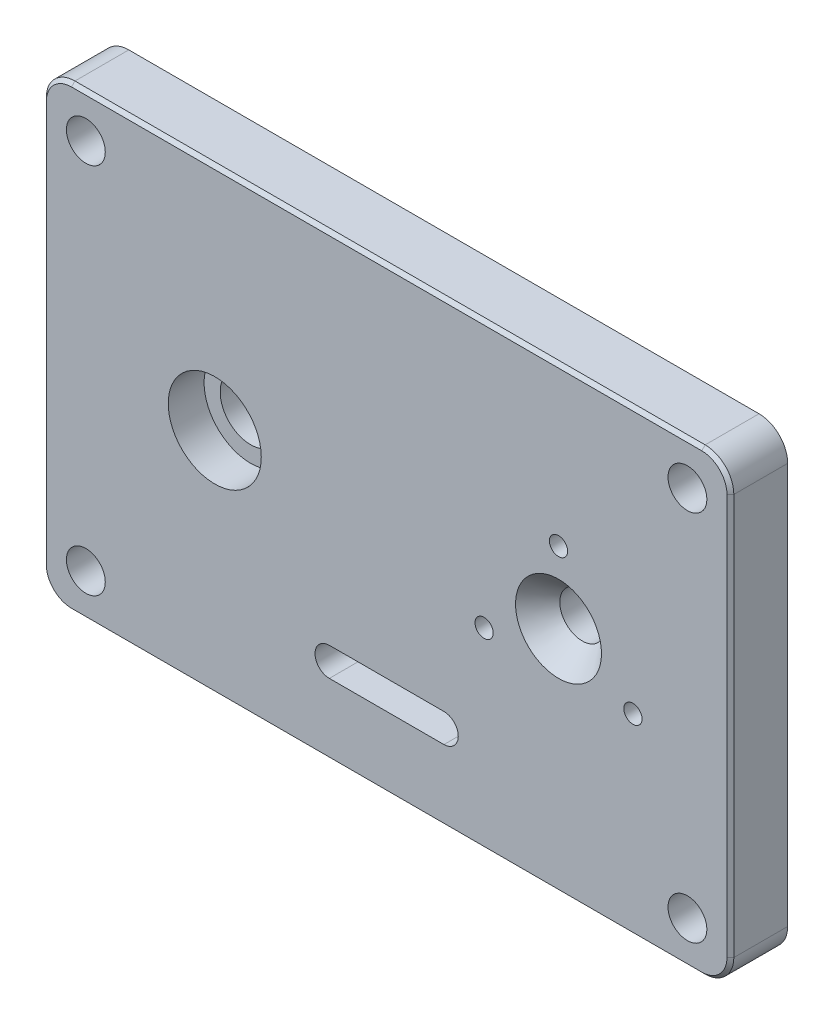
SolidWorks part; units mm, degrees
ref_plane "前视基准面" through (0, 0, 0) normal (0, 0, 1) x (1, 0, 0)
ref_plane "上视基准面" through (0, 0, 0) normal (0, 1, 0) x (1, 0, 0)
ref_plane "右视基准面" through (0, 0, 0) normal (1, 0, 0) x (0, 0, -1)
sketch "草图1" plane through (0, 0, 0) normal (0, 0, 1) x (1, 0, 0)
  line L0 (6.35, 0) -> (146.05, 0)
  line L1 (152.4, 6.35) -> (152.4, 95.25)
  line L2 (146.05, 101.6) -> (6.35, 101.6)
  line L3 (0, 95.25) -> (0, 6.35)
  arc A0 (0, 6.35) -> (6.35, 0) centre (6.35, 6.35) ccw
  arc A1 (146.05, 0) -> (152.4, 6.35) centre (146.05, 6.35) ccw
  arc A2 (152.4, 95.25) -> (146.05, 101.6) centre (146.05, 95.25) ccw
  arc A3 (6.35, 101.6) -> (0, 95.25) centre (6.35, 95.25) ccw
extrude "凸台-拉伸1" add sketch "草图1" along normal blind 12.7
ref_plane "基准面1" through (0, 0, 12.7) normal (0, 0, 1) x (1, 0, 0)
sketch "草图2" plane through (0, 0, 12.7) normal (0, 0, 1) x (1, 0, 0)
  circle A0 centre (9.525, 9.525) radius 4.3053
  circle A1 centre (142.875, 9.525) radius 4.3053
  circle A2 centre (9.525, 92.075) radius 4.3053
  circle A3 centre (142.875, 92.075) radius 4.3053
extrude "切除-拉伸1" cut sketch "草图2" against normal through all
sketch "草图3" plane through (0, 0, 12.7) normal (0, 0, 1) x (1, 0, 0)
  line L0 (63.5, 15.875) -> (88.9, 15.875)
  line L1 (88.9, 22.225) -> (63.5, 22.225)
  arc A0 (88.9, 15.875) -> (88.9, 22.225) centre (88.9, 19.05) ccw
  arc A1 (63.5, 22.225) -> (63.5, 15.875) centre (63.5, 19.05) ccw
extrude "切除-拉伸2" cut sketch "草图3" against normal through all
sketch "草图4" plane through (0, 0, 12.7) normal (0, 0, 1) x (1, 0, 0)
  circle A0 centre (38.1, 50.8) radius 10.3124
extrude "切除-拉伸3" cut sketch "草图4" against normal blind 7.9502
sketch "草图5" plane through (0, 0, 12.7) normal (0, 0, 1) x (1, 0, 0)
  circle A0 centre (38.1, 50.8) radius 6.7437
extrude "切除-拉伸4" cut sketch "草图5" against normal through all
sketch "草图6" plane through (0, 0, 12.7) normal (0, 0, 1) x (1, 0, 0)
  circle A0 centre (114.3, 50.8) radius 9.525
extrude "切除-拉伸5" cut sketch "草图6" against normal blind 5.2449 draft 41
sketch "草图7" plane through (0, 0, 12.7) normal (0, 0, 1) x (1, 0, 0)
  circle A0 centre (114.3, 50.8) radius 4.9657
extrude "切除-拉伸6" cut sketch "草图7" against normal through all
sketch "草图8" plane through (0, 0, 12.7) normal (0, 0, 1) x (1, 0, 0)
  circle A0 centre (114.3, 66.675) radius 2.0193
  circle A1 centre (97.802, 42.725) radius 2.0193
  circle A2 centre (130.798, 42.725) radius 2.0193
extrude "切除-拉伸7" cut sketch "草图8" against normal blind 9.525
chamfer "倒角1" distance 0.762 angle 45 8 edges at (150.5401, 99.7401, 12.7) (76.2, 101.6, 12.7) (1.8599, 99.7401, 12.7) (152.4, 50.8, 12.7) (150.5401, 1.8599, 12.7) (0, 50.8, 12.7) (1.8599, 1.8599, 12.7) (76.2, 0, 12.7)
